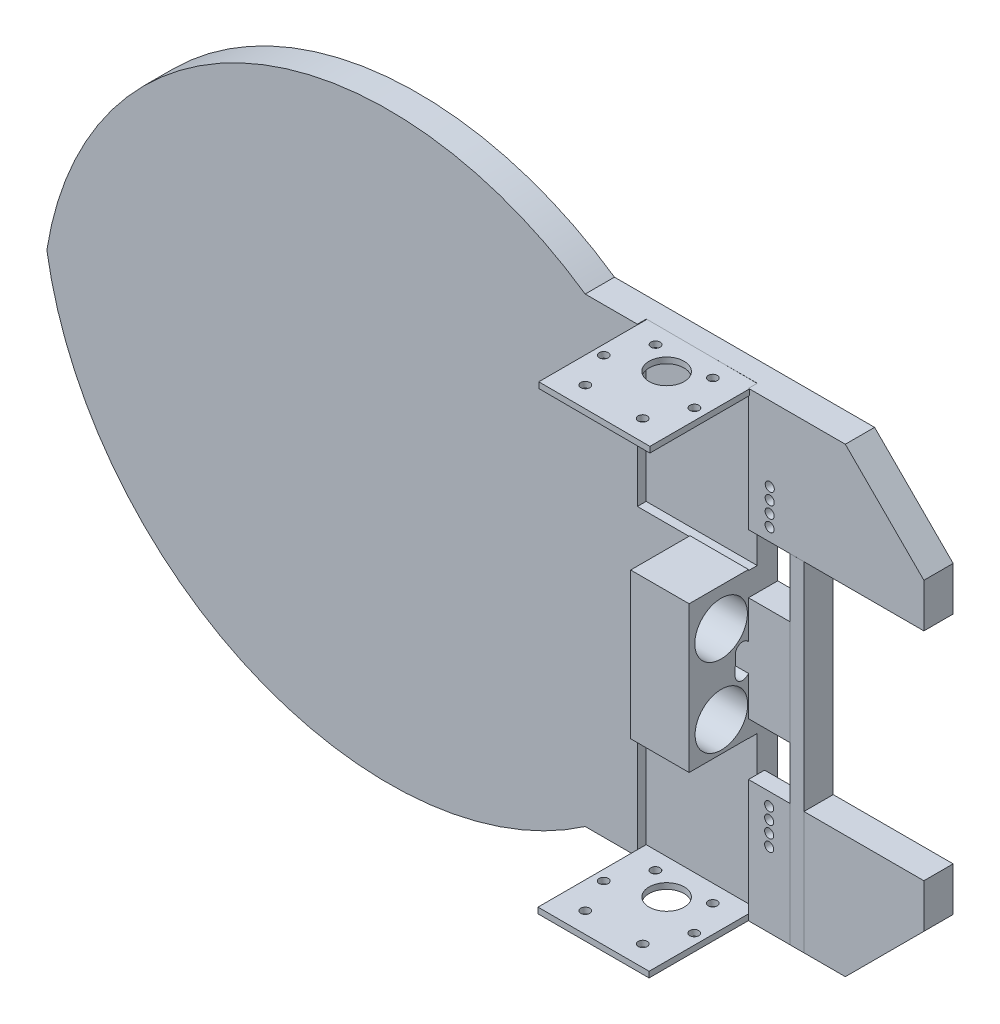
SolidWorks part; units mm, degrees
ref_plane "Front Plane" through (0, 0, 0) normal (0, 0, 1) x (1, 0, 0)
ref_plane "Top Plane" through (0, 0, 0) normal (0, 1, 0) x (1, 0, 0)
ref_plane "Right Plane" through (0, 0, 0) normal (1, 0, 0) x (0, 0, -1)
sketch "Sketch1" plane through (0, 0, 0) normal (0, 0, 1) x (1, 0, 0)
  line L1 (0, 0) -> (0, -37)
  line L2 (0, 37) -> (60, 37)
  line L3 (0, -37) -> (60, -37)
  line L4 (60, 37) -> (60, 52)
  line L5 (60, -37) -> (60, -52)
  line L6 (60, 52) -> (33.1299, 78.8701)
  line L7 (33.1299, 78.8701) -> (-55.8501, 78.8701)
  line L8 (60, -52) -> (33.1299, -78.8701)
  line L9 (33.1299, -78.8701) -> (-55.8501, -78.8701)
  line L10 (-55.8501, 78.8701) -> (-55.8501, 156.9436) construction
  line L11 (-55.8501, 156.9436) -> (-55.8501, -275.005) construction
  line L22 (0, 37) -> (0, 0)
  line L24 (-123.0632, 99.8019) -> (-270.1361, 99.8019) construction
  line L25 (-123.0632, 18.6512) -> (-123.0632, 134.1641) construction
  line L26 (-123.0632, -18.5763) -> (-123.0632, -116.9478) construction
  line L27 (-123.0632, -99.7887) -> (-269.8976, -99.7887) construction
  arc A7 (-239.9999, -0.1587) -> (-55.8501, 78.8701) centre (-123.0632, -18.5763) cw
  arc A8 (-55.8501, -78.8701) -> (-239.9999, -0.1587) centre (-123.0632, 18.6512) cw
  dimension "D11" = 199.5908
  dimension "D12" = 240
  dimension "D10" = 157.7401
  dimension "D1" = 37
  dimension "D2" = 37
  dimension "D3" = 60
  dimension "D4" = 15
  dimension "D5" = 15
  dimension "D6" = 135
  dimension "D7" = 38
  dimension "D8" = 38
  dimension "D9" = 135
  dimension "D15" = 88.98
  dimension "D16" = 88.98
extrude "Boss-Extrude1" add sketch "Sketch1" along normal blind 10 and the other way blind 0.01
sketch "Sketch3" plane through (0, 0, 10) normal (0, 0, 1) x (1, 0, 0)
  line L0 (33.1299, 78.8701) -> (-55.8501, 78.8701) construction
  line L1 (-38, 78.8701) -> (0, 78.8701)
  line L2 (-38, 78.8701) -> (-38, 24.8701)
  line L3 (-38, 24.8701) -> (0, 24.8701)
  line L4 (0, 78.8701) -> (0, 24.8701)
  dimension "D1" = 54
extrude "Cut-Extrude1" cut sketch "Sketch3" against normal blind 3 contours L2 L1 L4 L3
sketch "Sketch5" plane through (0, 0, 10) normal (0, 0, 1) x (1, 0, 0)
  line L0 (-55.8501, -78.8701) -> (33.1299, -78.8701) construction
  line L1 (-38, -24.8701) -> (0, -24.8701)
  line L2 (-38, -24.8701) -> (-38, -78.8701)
  line L3 (-38, -78.8701) -> (0, -78.8701)
  line L4 (0, -24.8701) -> (0, -78.8701)
  dimension "D1" = 54
extrude "Cut-Extrude3" cut sketch "Sketch5" against normal blind 3
sketch "Sketch7" plane through (0, 0, 10) normal (0, 0, 1) x (1, 0, 0)
  line L1 (-213.4131, 9.0562) -> (-44.4131, 9.0562)
  line L2 (-213.4131, 9.0562) -> (-213.4131, -48.9438)
  line L3 (-213.4131, -48.9438) -> (-44.4131, -48.9438)
  line L4 (-44.4131, 9.0562) -> (-44.4131, -48.9438)
  dimension "D1" = 58
  dimension "D2" = 169
extrude "Cut-Extrude4" [suppressed] cut sketch "Sketch7" against normal through all
sketch "Sketch8" plane through (0, 0, 10) normal (0, 0, 1) x (1, 0, 0)
  line L1 (-162.9927, 67.8133) -> (-84.7927, 67.8133)
  line L2 (-162.9927, 67.8133) -> (-162.9927, 10.3133)
  line L3 (-162.9927, 10.3133) -> (-84.7927, 10.3133)
  line L4 (-84.7927, 67.8133) -> (-84.7927, 10.3133)
  dimension "D1" = 78.2
  dimension "D2" = 57.5
extrude "Cut-Extrude5" [suppressed] cut sketch "Sketch8" against normal blind 3
sketch "Sketch9" plane through (0, 0, 10) normal (0, 0, 1) x (1, 0, 0)
  line L1 (-195, 36) -> (-176, 36)
  line L2 (-195, 36) -> (-195, 20)
  line L3 (-195, 20) -> (-176, 20)
  line L4 (-176, 36) -> (-176, 20)
  line L5 (-95.7317, 17.4542) -> (-82.493, 17.4542)
  line L6 (-95.7317, 17.4542) -> (-95.7317, 7.0108)
  line L7 (-95.7317, 7.0108) -> (-82.493, 7.0108)
  line L8 (-82.493, 17.4542) -> (-82.493, 7.0108)
  line L9 (-131.8867, -50.9252) -> (-116.9909, -50.9252)
  line L10 (-131.8867, -50.9252) -> (-131.8867, -65.1638)
  line L11 (-131.8867, -65.1638) -> (-116.9909, -65.1638)
  line L12 (-116.9909, -50.9252) -> (-116.9909, -65.1638)
extrude "Boss-Extrude2" [suppressed] add sketch "Sketch9" along normal blind 20.3
sketch "Sketch15" plane through (0, 0, 10) normal (0, 0, 1) x (1, 0, 0)
  line L0 (0, -24.8701) -> (0, 24.8701) construction
  line L1 (-20, 25.2016) -> (0, 25.2016)
  line L2 (-20, 25.2016) -> (-20, -24.7984)
  line L3 (-20, -24.7984) -> (0, -24.7984)
  line L4 (0, 25.2016) -> (0, -24.7984)
  dimension "D1" = 50
  dimension "D2" = 20
extrude "Boss-Extrude3" add sketch "Sketch15" along normal blind 20.3
sketch "Sketch16" plane through (0, 0, 10) normal (0, 0, 1) x (1, 0, 0)
  line L1 (-232.4208, 4) -> (-224.8235, 4)
  line L2 (-232.4208, 4) -> (-232.4208, -4)
  line L3 (-232.4208, -4) -> (-224.8235, -4)
  line L4 (-224.8235, 4) -> (-224.8235, -4)
  line L9 (-134.6881, 94.0493) -> (-144.6881, 94.0493)
  line L10 (-134.6881, 94.0493) -> (-134.6881, 84.6493)
  line L11 (-134.6881, 84.6493) -> (-144.6881, 84.6493)
  line L12 (-144.6881, 94.0493) -> (-144.6881, 84.6493)
  line L13 (-61.6779, 70.3488) -> (-70.3779, 70.3488)
  line L14 (-61.6779, 70.3488) -> (-61.6779, 61.8488)
  line L15 (-61.6779, 61.8488) -> (-70.3779, 61.8488)
  line L16 (-70.3779, 70.3488) -> (-70.3779, 61.8488)
  line L17 (-65.9779, -61.6233) -> (-75.3779, -61.6233)
  line L18 (-65.9779, -61.6233) -> (-65.9779, -70.9233)
  line L19 (-65.9779, -70.9233) -> (-75.3779, -70.9233)
  line L20 (-75.3779, -61.6233) -> (-75.3779, -70.9233)
  line L21 (-134.6881, -83.6815) -> (-144.6881, -83.6815)
  line L22 (-134.6881, -83.6815) -> (-134.6881, -92.9815)
  line L23 (-134.6881, -92.9815) -> (-144.6881, -92.9815)
  line L24 (-144.6881, -83.6815) -> (-144.6881, -92.9815)
extrude "Boss-Extrude4" [suppressed] add sketch "Sketch16" along normal blind 30
sketch "Sketch17" plane through (0, 0, 0) normal (0, 0, 1) x (1, 0, 0)
  circle A1 centre (-228.4208, 0) radius 2.55
  circle A2 centre (-139.6881, 89.6493) radius 3.5
  circle A3 centre (-65.8779, 66.3488) radius 3.5
  circle A4 centre (-69.8779, -66.6233) radius 3.5
  circle A5 centre (-139.6881, -88.6815) radius 3.5
extrude "Cut-Extrude17" [suppressed] cut sketch "Sketch17" along normal through all
sketch "Sketch18" plane through (0, 0, 10) normal (0, 0, 1) x (1, 0, 0)
  line L1 (-104.1245, 69) -> (-56.7245, 69)
  line L2 (-104.1245, 69) -> (-104.1245, 21.6)
  line L3 (-104.1245, 21.6) -> (-56.7245, 21.6)
  line L4 (-56.7245, 69) -> (-56.7245, 21.6)
  dimension "D1" = 47.4
  dimension "43.4" = 47.4
extrude "Cut-Extrude18" [suppressed] cut sketch "Sketch18" against normal through all
sketch "Sketch20" plane through (0, 0, 0) normal (0, 0, 1) x (1, 0, 0)
  circle A0 centre (-185.9471, 27.1121) radius 5
  circle A1 centre (-124.7094, -57.6129) radius 5
  circle A2 centre (-88.8879, 12.7504) radius 4
extrude "Cut-Extrude20" [suppressed] cut sketch "Sketch20" along normal through all
sketch "Sketch21" plane through (0, 0, 0) normal (1, 0, 0) x (0, 0, -1)
  line L0 (-3.8276, 29.0855) -> (-3.8276, -37.1575) construction
  line L1 (-6.4886, 28.3852) -> (-6.4886, -37.2976) construction
  line L2 (-5.0881, 28.1051) -> (-5.0881, -37.5777) construction
  line L3 (-11.99, 2.3019) -> (-12.0559, -4.1532) construction
  line L4 (-9.4916, 2.2764) -> (-9.5574, -4.1787)
  line L5 (-14.4885, 2.3274) -> (-14.5544, -4.1277)
  circle A0 centre (-19.3619, 12.3718) radius 9
  circle A1 centre (-19.2654, -14.6282) radius 9
  arc A2 (-9.4916, 2.2764) -> (-14.4885, 2.3274) centre (-11.99, 2.3019) ccw
  arc A3 (-14.5544, -4.1277) -> (-9.5574, -4.1787) centre (-12.0559, -4.1532) ccw
  point P12 (-12.023, -0.9256)
  dimension "D1" = 18
  dimension "D2" = 18
  dimension "D3" = 27
extrude "Cut-Extrude21" cut sketch "Sketch21" against normal up to surface (20 mm away) up to face at (-20, 5.1353, 18.12)
sketch "Sketch22" [suppressed] plane through (0, 0, 7) normal (0, 0, 1) x (1, 0, 0)
  circle A0 centre (-88.1686, 58.9795) radius 1.55
  circle A1 centre (-48.7686, 58.9795) radius 1.55
  circle A2 centre (-48.7686, 19.5795) radius 1.55
  circle A3 centre (-88.1686, 19.5795) radius 1.55
  dimension "D1" = 2
  dimension "D2" = 2
extrude "Cut-Extrude23" [suppressed] cut sketch "Sketch22" against normal through all
sketch "Sketch25" plane through (0, 0, 10) normal (0, 0, 1) x (1, 0, 0)
  line L1 (-173.6964, 70.8495) -> (-165.5964, 70.8495)
  line L2 (-173.6964, 70.8495) -> (-173.6964, 11.3495)
  line L3 (-173.6964, 11.3495) -> (-165.5964, 11.3495)
  line L4 (-165.5964, 70.8495) -> (-165.5964, 11.3495)
  dimension "D1" = 8.1
  dimension "D2" = 59.5
extrude "Boss-Extrude5" [suppressed] add sketch "Sketch25" along normal blind 3.5
sketch "Sketch26" [suppressed] plane through (0, 11.3495, 0) normal (0, -1, 0) x (1, 0, 0)
  line L0 (-172.679, 10.0037) -> (-152.674, 9.9893) construction
  line L1 (-152.674, 9.9893) -> (-152.6595, 14.6073) construction
  line L2 (-165.5928, 10.0085) -> (-173.4128, 10.0085)
  line L3 (-173.4128, 10.0085) -> (-173.4128, 12.4083)
  line L4 (-173.4128, 12.4083) -> (-165.5928, 12.4083)
  line L5 (-165.5928, 12.4083) -> (-165.5928, 10.0083)
  line M7 (-165.5964, 10) -> (-165.5964, 13.5)
extrude "Cut-Extrude24" [suppressed] cut sketch "Sketch26" against normal up to surface (59.5 mm away) contours L4 L3 L2 M7
sketch "Sketch28" plane through (0, -78.8701, 0) normal (0, -1, 0) x (1, 0, 0)
  line L1 (14.2266, 10.0076) -> (18.9795, 10.0076)
  line L2 (14.2266, 10.0076) -> (14.2266, 0.0598)
  line L3 (14.2266, 0.0598) -> (18.9795, 0.0598)
  line L4 (18.9795, 10.0076) -> (18.9795, 0.0598)
extrude "Boss-Extrude6" add sketch "Sketch28" against normal up to surface (115.8701 mm away) up to face at (24, 37, 5.396)
sketch "Sketch30" plane through (0, 0, -0.01) normal (0, 0, -1) x (-1, 0, 0)
  line L0 (0.5881, -0.0011) -> (-26.6848, -0.0585) construction
  line L1 (0, -62) -> (-14.12, -62)
  line L2 (0, -62) -> (0, -37)
  line L3 (0, -37) -> (-14.12, -37)
  line L4 (-14.12, -62) -> (-14.12, -37)
  line L5 (-14.3807, 61.9354) -> (-14.2755, 36.9356)
  line L6 (-0.1557, 36.995) -> (-14.2755, 36.9356)
  line L7 (-0.2608, 61.9948) -> (-0.1557, 36.995)
  line L8 (-0.2608, 61.9948) -> (-14.3807, 61.9354)
  dimension "D1" = 25
  dimension "D2" = 14.12
extrude "Cut-Extrude25" cut sketch "Sketch30" against normal blind 4.5
sketch "Sketch33" plane through (0, 0, -0.01) normal (0, 0, -1) x (-1, 0, 0)
  line L0 (0, 0) -> (-115.8951, -0.2361) construction
  circle A0 centre (-7.06, -53.4) radius 1.55
  circle A1 centre (-7.06, -49.4) radius 1.55
  circle A2 centre (-7.06, -45.4) radius 1.55
  circle A3 centre (-7.06, -41.4) radius 1.55
  circle A4 centre (-7.2286, 41.3709) radius 1.55
  circle A5 centre (-7.2449, 45.3709) radius 1.55
  circle A6 centre (-7.2612, 49.3708) radius 1.55
  circle A7 centre (-7.2775, 53.3708) radius 1.55
  dimension "D1" = 4
extrude "Cut-Extrude26" cut sketch "Sketch33" against normal up to surface (10.01 mm away) up to face at (7.1133, -57.935, 10)
sketch "Sketch34" plane through (0, 0, 10) normal (0, 0, 1) x (1, 0, 0)
  line L0 (0, 0) -> (85.4359, -0.2266) construction
  line L1 (53.8089, -34.3247) -> (61.9289, -40.2214)
  line L2 (53.8089, -34.3247) -> (57.1772, -29.6864)
  line L3 (61.9289, -40.2214) -> (65.2973, -35.5831)
  line L4 (57.1772, -29.6864) -> (65.2973, -35.5831)
  line L5 (62.1414, 39.8924) -> (65.4851, 35.2362)
  line L6 (57.3338, 29.3826) -> (65.4851, 35.2362)
  line L7 (53.9902, 34.0388) -> (57.3338, 29.3826)
  line L8 (53.9902, 34.0388) -> (62.1414, 39.8924)
extrude "Cut-Extrude27" [suppressed] cut sketch "Sketch34" against normal through all
sketch "Sketch36" plane through (0, 0, 7) normal (0, 0, 1) x (1, 0, 0)
  line L0 (0, 0) -> (106.9048, -0.1896) construction
  line L1 (0.2795, 78.8146) -> (0.2724, 76.8146)
  line L2 (0, -78.8151) -> (-38, -78.8151)
  line L3 (0, -78.8151) -> (0, -76.8151)
  line L4 (0, -76.8151) -> (-38, -76.8151)
  line L5 (-38, -78.8151) -> (-38, -76.8151)
  line L6 (-37.7202, 78.9494) -> (-37.7273, 76.9494)
  line L7 (0.2724, 76.8146) -> (-37.7273, 76.9494)
  line L8 (0.2795, 78.8146) -> (-37.7202, 78.9494)
  dimension "D1" = 2
extrude "Boss-Extrude7" add sketch "Sketch36" along normal blind 37
sketch "Sketch39" plane through (0, -78.8151, 0) normal (0, -1, 0) x (1, 0, 0)
  line L1 (-46.4365, 25) -> (22.9075, 25) construction
  line L4 (31.9978, 332) -> (-461.8231, 332) construction
  circle A1 centre (-19, 19) radius 6
  circle A2 centre (-34.4996, 25.0106) radius 1.55
  circle A3 centre (-3.5639, 24.9888) radius 1.55
  circle A4 centre (-28.8192, 37.0106) radius 1.55
  circle A5 centre (-9.1774, 36.9888) radius 1.55
  circle A6 centre (-28.82, 13.0106) radius 1.55
  circle A7 centre (-9.2305, 12.9888) radius 1.55
  point P18 (6.9989, 178.85)
  dimension "D1" = 12
  dimension "D5" = 12
  dimension "D6" = 12
  dimension "D7" = 12
  dimension "D8" = 12
  dimension "D2" = 19
extrude "Cut-Extrude28" cut sketch "Sketch39" against normal up to surface (2 mm away) up to face at (-19, -76.8151, 20.3333)
sketch "Sketch42" plane through (0.2795, 78.8146, 0) normal (0.0035, 1, 0) x (1, -0.0035, 0)
  circle A7 centre (-19.2797, -19) radius 6
  circle A9 centre (-29.0701, -13) radius 1.55
  circle A10 centre (-3.7784, -25) radius 1.55
  circle A11 centre (-9.4641, -13) radius 1.55
  circle A12 centre (-34.7723, -25) radius 1.55
  circle A13 centre (-29.0965, -37) radius 1.55
  circle A14 centre (-9.4734, -37) radius 1.55
  dimension "D1" = 12
  dimension "D5" = 6
  dimension "D6" = 6
  dimension "D7" = 6
  dimension "D8" = 6
  dimension "D9" = 18
  dimension "D10" = 18
  dimension "D2" = 19
extrude "Cut-Extrude29" cut sketch "Sketch42" against normal up to surface (2 mm away) up to face at (-12.485, 76.8599, 20.3333)
sketch "Sketch44" plane through (0, 0, -0.01) normal (0, 0, -1) x (-1, 0, 0)
  line L1 (-17.3212, 16.8295) -> (7.8547, 16.8295)
  line L2 (-17.3212, 16.8295) -> (-17.3212, -18.9977)
  line L3 (-17.3212, -18.9977) -> (7.8547, -18.9977)
  line L4 (7.8547, 16.8295) -> (7.8547, -18.9977)
extrude "Boss-Extrude8" add sketch "Sketch44" against normal up to surface (10.01 mm away) up to face at (5.7275, 53.3708, 10)
